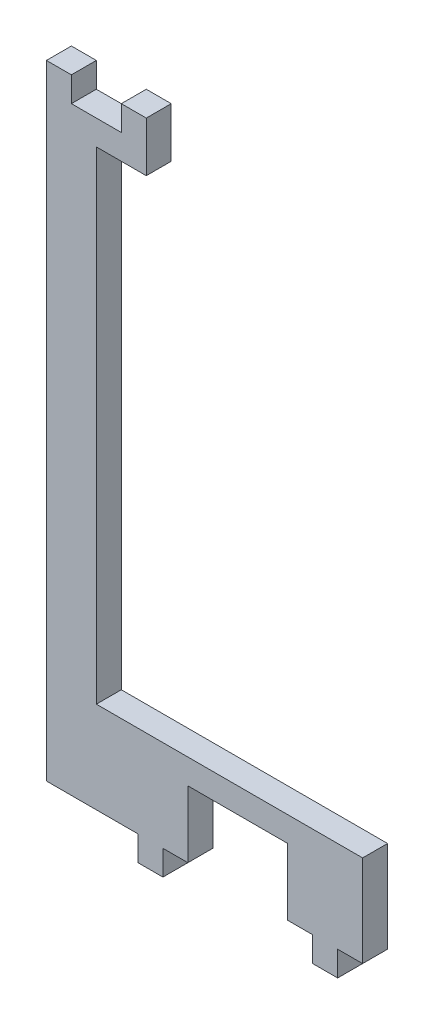
SolidWorks part; units mm, degrees
ref_plane "Alzado" through (0, 0, 0) normal (0, 0, 1) x (1, 0, 0)
ref_plane "Planta" through (0, 0, 0) normal (0, 1, 0) x (1, 0, 0)
ref_plane "Vista lateral" through (0, 0, 0) normal (1, 0, 0) x (0, 0, -1)
sketch "Croquis1" plane through (0, 0, 0) normal (0, 0, 1) x (1, 0, 0)
  line L17 (17, -69) -> (17, -61)
  line L18 (17, -61) -> (5, -61)
  line L19 (5, -61) -> (5, -69)
  line L21 (-12, -69) -> (-12, 3)
  line L24 (0, 0) -> (-6, 0)
  line L25 (-6, 0) -> (-6, -58)
  line L26 (-6, -58) -> (26, -58)
  line L27 (26, -58) -> (26, -69)
  line L30 (-12, 3) -> (-12, 6)
  line L31 (-12, 6) -> (-9, 6)
  line L32 (-9, 6) -> (-9, 3)
  line L35 (-12, -69) -> (-1, -69)
  line L36 (-1, -69) -> (-1, -72)
  line L37 (-1, -72) -> (2, -72)
  line L38 (2, -72) -> (2, -69)
  line L39 (2, -69) -> (5, -69)
  line L40 (17, -69) -> (20, -69)
  line L41 (20, -69) -> (20, -72)
  line L42 (20, -72) -> (23, -72)
  line L43 (23, -72) -> (23, -69)
  line L44 (23, -69) -> (26, -69)
  line L45 (-9, 3) -> (-3, 3)
  line L46 (-3, 3) -> (-3, 6)
  line L47 (-3, 6) -> (0, 6)
  line L48 (0, 6) -> (0, 0)
  point P2 (4.1456, 6.3985)
  point P3 (15.0096, 4.2331)
  point P7 (0, 0)
  point P17 (-0.1325, 5.953)
  point P29 (-7.1687, 3.7014)
  point P30 (-1.4271, -32.1555)
  point P31 (-11.9158, -46.185)
  point P32 (0, 0)
  dimension "D1" = 3
  dimension "D2" = 6
  dimension "D3" = 6
  dimension "D4" = 12
  dimension "D5" = 8
  dimension "D6" = 72
  dimension "D7" = 11
  dimension "D8" = 17
extrude "Saliente-Extruir1" add sketch "Croquis1" along normal blind 3
